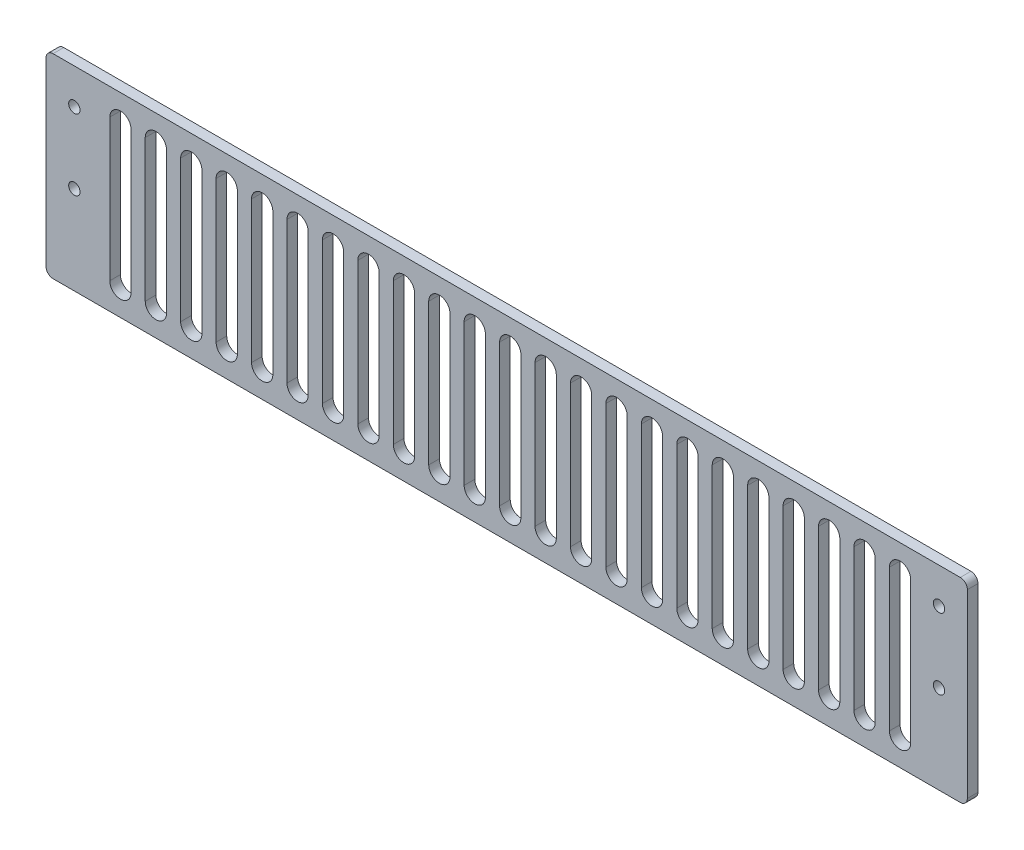
SolidWorks part; units mm, degrees
material "Thornel Mat VMA"
ref_plane "前视基准面" through (0, 0, 0) normal (0, 0, 1) x (1, 0, 0)
ref_plane "上视基准面" through (0, 0, 0) normal (0, 1, 0) x (1, 0, 0)
ref_plane "右视基准面" through (0, 0, 0) normal (1, 0, 0) x (0, 0, -1)
other "Configuration Table"
sketch "草图1" plane through (0, 0, 0) normal (0, 0, 1) x (1, 0, 0)
  line L1 (130, -27.5) -> (-130, -27.5)
  line L2 (130, -27.5) -> (130, 27.5)
  line L3 (130, 27.5) -> (-130, 27.5)
  line L4 (-130, -27.5) -> (-130, 27.5)
  line L5 (130, -27.5) -> (-130, 27.5) construction
  line L6 (130, 27.5) -> (-130, -27.5) construction
  point P0 (0, 0)
  dimension "D1" = 260
  dimension "D2" = 55
extrude "凸台-拉伸1" add sketch "草图1" along normal blind 3
fillet "圆角1" radius 2 4 edges at (130, 27.5, 1.5) (130, -27.5, 1.5) (-130, -27.5, 1.5) (-130, 27.5, 1.5)
sketch "草图2" plane through (0, 0, 3) normal (0, 0, 1) x (1, 0, 0)
  line L0 (0, 27.5) -> (0, -27.5) construction
  line L1 (128, 27.5) -> (-128, 27.5) construction
  line L2 (-128, -27.5) -> (128, -27.5) construction
  line L3 (-122, 27.5) -> (-122, -27.5) construction
  line L4 (-130, 25.5) -> (-130, -25.5) construction
  circle A0 centre (-122, 17.5) radius 1.6
  circle A1 centre (-122, -2.5) radius 1.6
  circle A2 centre (122, -2.5) radius 1.6
  circle A3 centre (122, 17.5) radius 1.6
  dimension "D1" = 3.2
  dimension "D2" = 10
  dimension "D3" = 20
  dimension "D4" = 8
extrude "切除-拉伸1" cut sketch "草图2" against normal blind 18
sketch "草图3" plane through (0, 0, 3) normal (0, 0, 1) x (1, 0, 0)
  line L9 (-109, 20) -> (-109, -20) construction
  line L14 (-106, 20) -> (-106, -20)
  line L15 (-112, 20) -> (-112, -20)
  line L16 (-130, 0) -> (130, 0) construction
  line L17 (-130, 25.5) -> (-130, -25.5) construction
  line L18 (130, -25.5) -> (130, 25.5) construction
  line L19 (-99, 20) -> (-99, -20) construction
  line L20 (-96, 20) -> (-96, -20)
  line L21 (-102, 20) -> (-102, -20)
  line L22 (-89, 20) -> (-89, -20) construction
  line L23 (-86, 20) -> (-86, -20)
  line L24 (-92, 20) -> (-92, -20)
  line L25 (-79, 20) -> (-79, -20) construction
  line L26 (-76, 20) -> (-76, -20)
  line L27 (-82, 20) -> (-82, -20)
  line L28 (-69, 20) -> (-69, -20) construction
  line L29 (-66, 20) -> (-66, -20)
  line L30 (-72, 20) -> (-72, -20)
  line L31 (-59, 20) -> (-59, -20) construction
  line L32 (-56, 20) -> (-56, -20)
  line L33 (-62, 20) -> (-62, -20)
  line L34 (-49, 20) -> (-49, -20) construction
  line L35 (-46, 20) -> (-46, -20)
  line L36 (-52, 20) -> (-52, -20)
  line L37 (-39, 20) -> (-39, -20) construction
  line L38 (-36, 20) -> (-36, -20)
  line L39 (-42, 20) -> (-42, -20)
  line L40 (-29, 20) -> (-29, -20) construction
  line L41 (-26, 20) -> (-26, -20)
  line L42 (-32, 20) -> (-32, -20)
  line L43 (-19, 20) -> (-19, -20) construction
  line L44 (-16, 20) -> (-16, -20)
  line L45 (-22, 20) -> (-22, -20)
  line L46 (-9, 20) -> (-9, -20) construction
  line L47 (-6, 20) -> (-6, -20)
  line L48 (-12, 20) -> (-12, -20)
  line L49 (1, 20) -> (1, -20) construction
  line L50 (4, 20) -> (4, -20)
  line L51 (-2, 20) -> (-2, -20)
  line L52 (11, 20) -> (11, -20) construction
  line L53 (14, 20) -> (14, -20)
  line L54 (8, 20) -> (8, -20)
  line L55 (21, 20) -> (21, -20) construction
  line L56 (24, 20) -> (24, -20)
  line L57 (18, 20) -> (18, -20)
  line L58 (31, 20) -> (31, -20) construction
  line L59 (34, 20) -> (34, -20)
  line L60 (28, 20) -> (28, -20)
  line L61 (41, 20) -> (41, -20) construction
  line L62 (44, 20) -> (44, -20)
  line L63 (38, 20) -> (38, -20)
  line L64 (51, 20) -> (51, -20) construction
  line L65 (54, 20) -> (54, -20)
  line L66 (48, 20) -> (48, -20)
  line L67 (61, 20) -> (61, -20) construction
  line L68 (64, 20) -> (64, -20)
  line L69 (58, 20) -> (58, -20)
  line L70 (71, 20) -> (71, -20) construction
  line L71 (74, 20) -> (74, -20)
  line L72 (68, 20) -> (68, -20)
  line L73 (81, 20) -> (81, -20) construction
  line L74 (84, 20) -> (84, -20)
  line L75 (78, 20) -> (78, -20)
  line L76 (91, 20) -> (91, -20) construction
  line L77 (94, 20) -> (94, -20)
  line L78 (88, 20) -> (88, -20)
  line L79 (101, 20) -> (101, -20) construction
  line L80 (104, 20) -> (104, -20)
  line L81 (98, 20) -> (98, -20)
  line L82 (111, 20) -> (111, -20) construction
  line L83 (114, 20) -> (114, -20)
  line L84 (108, 20) -> (108, -20)
  arc A0 (-106, 20) -> (-112, 20) centre (-109, 20) ccw
  arc A1 (-112, -20) -> (-106, -20) centre (-109, -20) ccw
  arc A2 (-96, 20) -> (-102, 20) centre (-99, 20) ccw
  arc A3 (-102, -20) -> (-96, -20) centre (-99, -20) ccw
  arc A4 (-86, 20) -> (-92, 20) centre (-89, 20) ccw
  arc A5 (-92, -20) -> (-86, -20) centre (-89, -20) ccw
  arc A6 (-76, 20) -> (-82, 20) centre (-79, 20) ccw
  arc A7 (-82, -20) -> (-76, -20) centre (-79, -20) ccw
  arc A8 (-66, 20) -> (-72, 20) centre (-69, 20) ccw
  arc A9 (-72, -20) -> (-66, -20) centre (-69, -20) ccw
  arc A10 (-56, 20) -> (-62, 20) centre (-59, 20) ccw
  arc A11 (-62, -20) -> (-56, -20) centre (-59, -20) ccw
  arc A12 (-46, 20) -> (-52, 20) centre (-49, 20) ccw
  arc A13 (-52, -20) -> (-46, -20) centre (-49, -20) ccw
  arc A14 (-36, 20) -> (-42, 20) centre (-39, 20) ccw
  arc A15 (-42, -20) -> (-36, -20) centre (-39, -20) ccw
  arc A16 (-26, 20) -> (-32, 20) centre (-29, 20) ccw
  arc A17 (-32, -20) -> (-26, -20) centre (-29, -20) ccw
  arc A18 (-16, 20) -> (-22, 20) centre (-19, 20) ccw
  arc A19 (-22, -20) -> (-16, -20) centre (-19, -20) ccw
  arc A20 (-6, 20) -> (-12, 20) centre (-9, 20) ccw
  arc A21 (-12, -20) -> (-6, -20) centre (-9, -20) ccw
  arc A22 (4, 20) -> (-2, 20) centre (1, 20) ccw
  arc A23 (-2, -20) -> (4, -20) centre (1, -20) ccw
  arc A24 (14, 20) -> (8, 20) centre (11, 20) ccw
  arc A25 (8, -20) -> (14, -20) centre (11, -20) ccw
  arc A26 (24, 20) -> (18, 20) centre (21, 20) ccw
  arc A27 (18, -20) -> (24, -20) centre (21, -20) ccw
  arc A28 (34, 20) -> (28, 20) centre (31, 20) ccw
  arc A29 (28, -20) -> (34, -20) centre (31, -20) ccw
  arc A30 (44, 20) -> (38, 20) centre (41, 20) ccw
  arc A31 (38, -20) -> (44, -20) centre (41, -20) ccw
  arc A32 (54, 20) -> (48, 20) centre (51, 20) ccw
  arc A33 (48, -20) -> (54, -20) centre (51, -20) ccw
  arc A34 (64, 20) -> (58, 20) centre (61, 20) ccw
  arc A35 (58, -20) -> (64, -20) centre (61, -20) ccw
  arc A36 (74, 20) -> (68, 20) centre (71, 20) ccw
  arc A37 (68, -20) -> (74, -20) centre (71, -20) ccw
  arc A38 (84, 20) -> (78, 20) centre (81, 20) ccw
  arc A39 (78, -20) -> (84, -20) centre (81, -20) ccw
  arc A40 (94, 20) -> (88, 20) centre (91, 20) ccw
  arc A41 (88, -20) -> (94, -20) centre (91, -20) ccw
  arc A42 (104, 20) -> (98, 20) centre (101, 20) ccw
  arc A43 (98, -20) -> (104, -20) centre (101, -20) ccw
  arc A44 (114, 20) -> (108, 20) centre (111, 20) ccw
  arc A45 (108, -20) -> (114, -20) centre (111, -20) ccw
  point P2 (-109, 0)
  point P12 (0, 0)
  point P19 (-99, 0)
  point P26 (-89, 0)
  point P33 (-79, 0)
  point P40 (-69, 0)
  point P47 (-59, 0)
  point P54 (-49, 0)
  point P61 (-39, 0)
  point P68 (-29, 0)
  point P75 (-19, 0)
  point P82 (-9, 0)
  point P89 (1, 0)
  point P96 (11, 0)
  point P103 (21, 0)
  point P110 (31, 0)
  point P117 (41, 0)
  point P124 (51, 0)
  point P131 (61, 0)
  point P138 (71, 0)
  point P145 (81, 0)
  point P152 (91, 0)
  point P159 (101, 0)
  point P166 (111, 0)
  dimension "D1" = 3
  dimension "D2" = 40
  dimension "D3" = 18
  dimension "D4" = 23
extrude "切除-拉伸2" cut sketch "草图3" against normal blind 10
